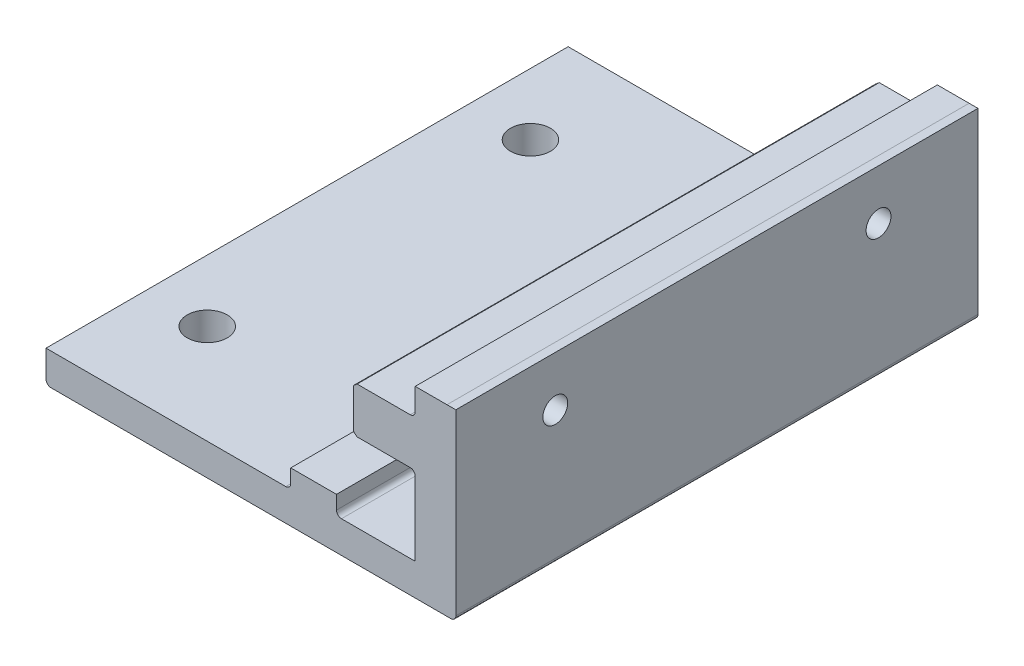
SolidWorks part; units mm, degrees
ref_plane "Front Plane" through (0, 0, 0) normal (0, 0, 1) x (1, 0, 0)
ref_plane "Top Plane" through (0, 0, 0) normal (0, 1, 0) x (1, 0, 0)
ref_plane "Right Plane" through (0, 0, 0) normal (1, 0, 0) x (0, 0, -1)
ref_plane "Plane1" through (0, 0, -3683) normal (0, 0, -1) x (-1, 0, 0)
sketch "Sketch1" plane through (0, 0, -3683) normal (0, 0, -1) x (-1, 0, 0)
  line L0 (7.9453, 3.5889) -> (-1.1987, 3.5889)
  line L1 (-1.8337, 4.2239) -> (-1.8337, 5.7479)
  line L2 (-1.1987, 6.3829) -> (1.6216, 6.3829)
  line L3 (1.6216, 6.3829) -> (1.6216, 6.8909)
  line L4 (1.6216, 6.8909) -> (-2.2147, 11.4629)
  line L5 (-2.2147, 11.4629) -> (-7.2947, 11.4629)
  line L6 (-7.2947, 11.4629) -> (-11.1311, 6.8909)
  line L7 (-11.1311, 6.8909) -> (-11.1311, 6.3829)
  line L8 (-11.1311, 6.3829) -> (-8.3107, 6.3829)
  line L9 (-7.6757, 5.7479) -> (-7.6757, 4.2239)
  line L10 (-8.3107, 3.5889) -> (-17.4547, 3.5889)
  line L11 (-17.7279, 3.8588) -> (-17.7284, 13.0024)
  line L12 (-17.4548, -0.4751) -> (7.9452, -0.4751)
  line L13 (-17.0929, 13.6378) -> (-15.5689, 13.6378)
  line L29 (-17.4547, 3.5889) -> (-17.7279, 3.5889)
  line L30 (-17.4548, -0.4751) -> (-17.7279, -0.4751)
  line L32 (8.2155, 3.5889) -> (8.2155, -0.4751)
  line L34 (8.2155, 3.5889) -> (7.9453, 3.5889)
  line L35 (8.2155, -0.4751) -> (7.9452, -0.4751)
  line L36 (-14.9339, 13.0028) -> (-14.9339, 10.1825)
  line L37 (-14.9339, 10.1825) -> (-14.4259, 10.1825)
  line L38 (-14.4259, 10.1825) -> (-9.8539, 14.0188)
  line L39 (-9.8539, 14.0188) -> (-9.8539, 19.0988)
  line L40 (-9.8539, 19.0988) -> (-14.4259, 22.9352)
  line L41 (-14.4259, 22.9352) -> (-14.9339, 22.9352)
  line L42 (-14.9339, 22.9352) -> (-14.9339, 20.1148)
  line L43 (-15.5689, 19.4798) -> (-17.0929, 19.4798)
  line L44 (-17.7287, 20.1156) -> (-17.7288, 22.9352)
  line L45 (-21.7872, 22.9352) -> (-21.7919, 3.8591)
  line L49 (-17.7288, 22.9352) -> (-21.7872, 22.9352)
  line L51 (-17.7279, 3.5889) -> (-17.7279, 3.8588)
  line L52 (-21.7919, 3.5889) -> (-21.7919, 3.8591)
  line L54 (-17.7279, -0.4751) -> (-21.7919, -0.4751)
  line L56 (-21.7919, -0.4751) -> (-21.7919, 3.5889)
  arc A0 (-1.1987, 3.5889) -> (-1.8337, 4.2239) centre (-1.1987, 4.2239) cw
  arc A1 (-1.8337, 5.7479) -> (-1.1987, 6.3829) centre (-1.1987, 5.7479) cw
  arc A2 (-8.3107, 6.3829) -> (-7.6757, 5.7479) centre (-8.3107, 5.7479) cw
  arc A3 (-7.6757, 4.2239) -> (-8.3107, 3.5889) centre (-8.3107, 4.2239) cw
  arc A4 (-17.7284, 13.0024) -> (-17.0929, 13.6378) centre (-17.0929, 13.0024) cw
  arc A5 (-15.5689, 13.6378) -> (-14.9339, 13.0028) centre (-15.5689, 13.0028) cw
  arc A6 (-14.9339, 20.1148) -> (-15.5689, 19.4798) centre (-15.5689, 20.1148) cw
  arc A7 (-17.0929, 19.4798) -> (-17.7287, 20.1156) centre (-17.0929, 20.1156) cw
extrude "Boss-Extrude1" add sketch "Sketch1" along normal blind 66.675
sketch "Sketch2" plane through (0, 0, -3683) normal (0, 0, 1) x (1, 0, 0)
  line L0 (11.1311, 6.8909) -> (11.1311, 6.3829) construction
  line L1 (11.1311, 6.3829) -> (8.3107, 6.3829) construction
  line L2 (7.2947, 11.4629) -> (11.1311, 6.8909) construction
  line L3 (4.7547, 11.4629) -> (4.7547, -3.7872) construction
  line L4 (7.6757, 5.7479) -> (7.6757, 4.2239) construction
  line L5 (11.1311, 6.8909) -> (11.1311, 6.3829)
  line L6 (11.1311, 6.3829) -> (8.3107, 6.3829)
  line L7 (7.6757, 11.0088) -> (11.1311, 6.8909)
  line L8 (2.2147, 11.4629) -> (7.2947, 11.4629) construction
  line L9 (7.6757, 5.7479) -> (7.6757, 11.0088)
  line L10 (1.8337, 5.7479) -> (1.8337, 11.0088)
  line L11 (1.8337, 11.0088) -> (-1.6216, 6.8909)
  line L12 (-1.6216, 6.3829) -> (1.1987, 6.3829)
  line L13 (-1.6216, 6.8909) -> (-1.6216, 6.3829)
  arc A0 (8.3107, 6.3829) -> (7.6757, 5.7479) centre (8.3107, 5.7479) ccw construction
  arc A1 (8.3107, 6.3829) -> (7.6757, 5.7479) centre (8.3107, 5.7479) ccw
  arc A2 (1.1987, 6.3829) -> (1.8337, 5.7479) centre (1.1987, 5.7479) cw
extrude "Cut-Extrude1" cut sketch "Sketch2" against normal up to next
sketch "Sketch3" plane through (0, 0, -3683) normal (0, 0, 1) x (1, 0, 0)
  line L0 (15.5689, 19.4798) -> (17.0929, 19.4798) construction
  line L1 (14.9339, 22.9352) -> (14.9339, 20.1148) construction
  line L2 (14.4259, 22.9352) -> (14.9339, 22.9352) construction
  line L3 (9.8539, 19.0988) -> (14.4259, 22.9352) construction
  line L4 (15.5689, 19.4798) -> (10.308, 19.4798)
  line L5 (14.9339, 22.9352) -> (14.9339, 20.1148)
  line L6 (14.4259, 22.9352) -> (14.9339, 22.9352)
  line L7 (10.308, 19.4798) -> (14.4259, 22.9352)
  line L8 (9.8539, 16.5588) -> (24.7491, 16.5588) construction
  line L9 (9.8539, 14.0188) -> (9.8539, 19.0988) construction
  line L10 (10.308, 13.6378) -> (14.4259, 10.1825)
  line L11 (14.4259, 10.1825) -> (14.9339, 10.1825)
  line L12 (14.9339, 10.1825) -> (14.9339, 13.0028)
  line L13 (15.5689, 13.6378) -> (10.308, 13.6378)
  arc A0 (14.9339, 20.1148) -> (15.5689, 19.4798) centre (15.5689, 20.1148) ccw construction
  arc A1 (14.9339, 20.1148) -> (15.5689, 19.4798) centre (15.5689, 20.1148) ccw
  arc A2 (14.9339, 13.0028) -> (15.5689, 13.6378) centre (15.5689, 13.0028) cw
extrude "Cut-Extrude2" cut sketch "Sketch3" against normal up to next
sketch "Sketch4" plane through (0, 0, -3683) normal (0, 0, 1) x (1, 0, 0)
  line L0 (2.2147, 11.4629) -> (7.2947, 11.4629) construction
  line L1 (9.8539, 14.0188) -> (9.8539, 19.0988) construction
  point P0 (4.7547, 11.4629)
  point P1 (9.8539, 16.5588)
sketch "Sketch6" plane through (-8.2155, 0, 0) normal (-1, 0, 0) x (0, 0, 1)
  line L1 (-3749.675, 3.5889) -> (-3683, 3.5889)
  line L2 (-3749.675, 3.5889) -> (-3749.675, -0.4751)
  line L3 (-3749.675, -0.4751) -> (-3683, -0.4751)
  line L4 (-3683, 3.5889) -> (-3683, -0.4751)
extrude "Boss-Extrude2" add sketch "Sketch6" along normal blind 22.2174
hole_wizard "#10 Clearance Hole1" positions "Sketch7" profile "Sketch8" hole size "#10" standard "ANSI Inch" end condition up to next
sketch "Sketch7" plane through (0, 3.5889, 0) normal (0, 1, 0) x (1, 0, 0)
  line L0 (-30.4329, 3683) -> (-30.4329, 3749.675) construction
  line L1 (-30.4329, 3749.675) -> (1.1987, 3749.675) construction
  line L2 (-30.4329, 3683) -> (1.1987, 3683) construction
  point P0 (-21.5302, 3736.975)
  point P2 (-21.5302, 3695.7)
  dimension "D1" = 8.9027
  dimension "D2" = 8.9027
  dimension "D3" = 12.7
  dimension "D4" = 12.7
sketch "Sketch8" plane through (-21.5302, 3.5889, -3736.975) normal (1, 0, 0) x (0, 0, 1)
  line L0 (0, 0) -> (0, 4.064)
  line L1 (0, 4.064) -> (2.5527, 4.064)
  line L2 (2.5527, 4.064) -> (2.5527, 0)
  line L5 (2.5527, 0) -> (0, 0)
  line L11 (0, -6.35) -> (0, 107.95) construction
  dimension "Thru Hole Dia." = 5.1054
  dimension "Thru Hole Depth" = 4.064
sketch "Sketch12" plane through (0, 0, -3749.675) normal (0, 0, -1) x (-1, 0, 0)
  line L0 (-7.6757, 11.0088) -> (-7.6757, 4.2239) construction
  line L1 (-7.6757, 5.9701) -> (-1.8337, 5.9701)
  line L2 (-7.6757, 5.9701) -> (-7.6757, 11.4629)
  line L3 (-7.6757, 11.4629) -> (-1.8337, 11.4629)
  line L4 (-1.8337, 5.9701) -> (-1.8337, 11.4629)
  line L5 (-2.2147, 11.4629) -> (-7.2947, 11.4629) construction
  line L11 (-1.8337, 4.2239) -> (-1.8337, 11.0088) construction
  line L12 (-8.3107, 3.5889) -> (-17.7279, 3.5889) construction
  point P10 (-1.8337, 7.6163)
  dimension "D1" = 0
  dimension "D2" = 2.3813
extrude "Cut-Extrude4" cut sketch "Sketch12" against normal through all
hole_wizard "#4 Clearance Hole1" positions "Sketch15" profile "Sketch14" hole size "#4" standard "ANSI Inch" end condition through all
sketch "Sketch15" plane through (0, 5.9701, 0) normal (0, 1, 0) x (1, 0, 0)
  line L0 (7.6757, 3749.675) -> (1.8337, 3749.675) construction
  line L1 (7.6757, 3683) -> (1.8337, 3683) construction
  line L3 (1.8337, 3683) -> (1.8337, 3749.675) construction
  line L4 (7.6757, 3683) -> (7.6757, 3749.675) construction
  point P0 (4.7547, 3736.975)
  point P2 (4.7547, 3695.7)
  dimension "D1" = 12.7
  dimension "D2" = 12.7
  dimension "D3" = 2.921
  dimension "D4" = 2.921
sketch "Sketch14" plane through (4.7547, 5.9701, -3736.975) normal (1, 0, 0) x (0, 0, 1)
  line L0 (0, 0) -> (0, 6.4453)
  line L1 (0, 6.4453) -> (1.6319, 6.4453)
  line L2 (1.6319, 6.4453) -> (1.6319, 0)
  line L5 (1.6319, 0) -> (0, 0)
  line L11 (0, -6.35) -> (0, 107.95) construction
  dimension "Thru Hole Dia." = 3.2639
  dimension "Thru Hole Depth" = 6.4453
sketch "Sketch19" plane through (21.7929, 0.0054, 0) normal (1, 0.0002, 0) x (0, 0, -1)
  line L0 (3749.675, 22.9298) -> (3749.675, 3.8538) construction
  line L1 (3683, 22.9298) -> (3749.675, 22.9298)
  line L2 (3683, 22.9298) -> (3683, -0.4805)
  line L3 (3683, -0.4805) -> (3749.675, -0.4805)
  line L4 (3749.675, 22.9298) -> (3749.675, -0.4805)
  line L5 (3749.675, -0.4805) -> (3683, -0.4805) construction
  dimension "D1" = 0
extrude "Boss-Extrude7" add sketch "Sketch19" along normal blind 1.1278
hole_wizard "1/8 (0.1250) Dowel Hole1" positions "Sketch16" profile "Sketch17" hole size "1/8" standard "ANSI Inch" end condition through all
sketch "Sketch16" plane through (9.8539, 0, 0) normal (-1, 0, 0) x (0, 0, 1)
  line L0 (-3749.675, 14.0188) -> (-3749.675, 19.0988) construction
  line L1 (-3683, 14.0188) -> (-3683, 19.0988) construction
  line L2 (-3749.675, 19.0988) -> (-3683, 19.0988) construction
  line L4 (-3749.675, 14.0188) -> (-3683, 14.0188) construction
  point P0 (-3736.975, 16.5588)
  point P2 (-3695.7, 16.5588)
  dimension "D1" = 12.7
  dimension "D2" = 12.7
  dimension "D3" = 2.54
  dimension "D4" = 2.54
sketch "Sketch17" plane through (9.8539, 16.5588, -3736.975) normal (0, 1, 0) x (0, 0, 1)
  line L0 (0, 0) -> (0, 13.0668)
  line L1 (0, 13.0668) -> (1.5875, 13.0668)
  line L2 (1.5875, 13.0668) -> (1.5875, 0)
  line L5 (1.5875, 0) -> (0, 0)
  line L11 (0, -6.35) -> (0, 107.95) construction
  dimension "Thru Hole Dia." = 3.175
  dimension "Thru Hole Depth" = 13.0668
sketch "Sketch20" plane through (0, 0, -3683) normal (0, 0, 1) x (1, 0, 0)
  line L0 (21.7919, -0.4751) -> (-30.4329, -0.4751) construction
  line L1 (-29.4169, -0.4751) -> (-30.4329, -0.4751)
  line L2 (-29.4169, -0.4751) -> (-29.4169, 3.5889)
  line L3 (-29.4169, 3.5889) -> (-30.4329, 3.5889)
  line L4 (-30.4329, -0.4751) -> (-30.4329, 3.5889)
  dimension "D1" = 1.016
extrude "Cut-Extrude5" cut sketch "Sketch20" against normal through all
fillet "Fillet1" radius 0.635 2 edges at (-29.4169, -0.4751, -3716.3375) (22.9208, -0.4749, -3716.3375)
